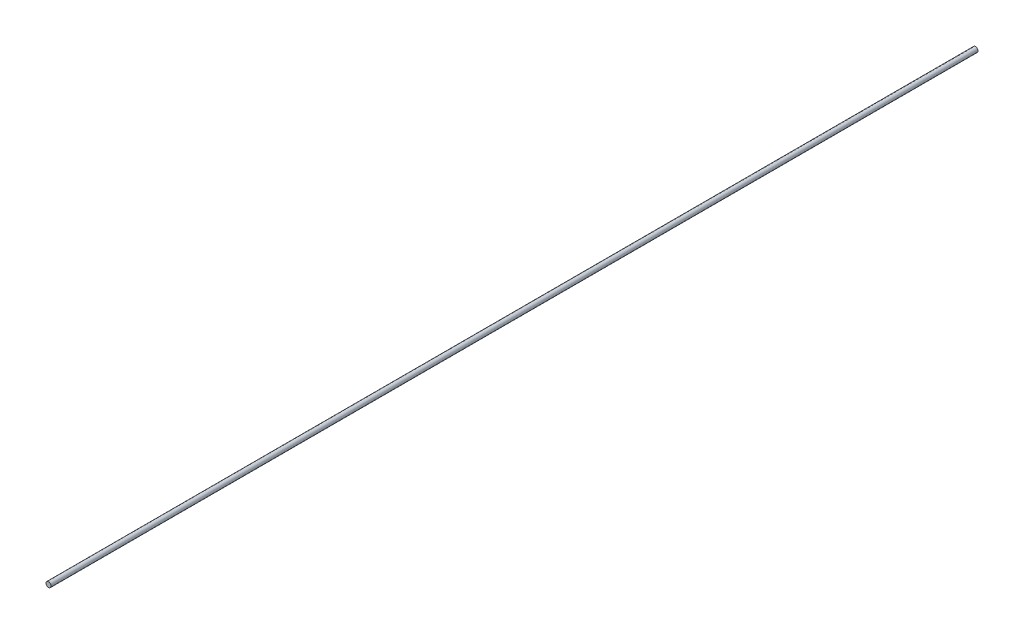
SolidWorks part; units mm, degrees
ref_plane "Front Plane" through (0, 0, 0) normal (0, 0, 1) x (1, 0, 0)
ref_plane "Top Plane" through (0, 0, 0) normal (0, 1, 0) x (1, 0, 0)
ref_plane "Right Plane" through (0, 0, 0) normal (1, 0, 0) x (0, 0, -1)
sketch "Sketch1" plane through (0, 0, 0) normal (0, 0, 1) x (1, 0, 0)
  circle A0 centre (0, 0) radius 1.25
  dimension "D1" = 2.5
extrude "Boss-Extrude1" add sketch "Sketch1" along normal blind 460
